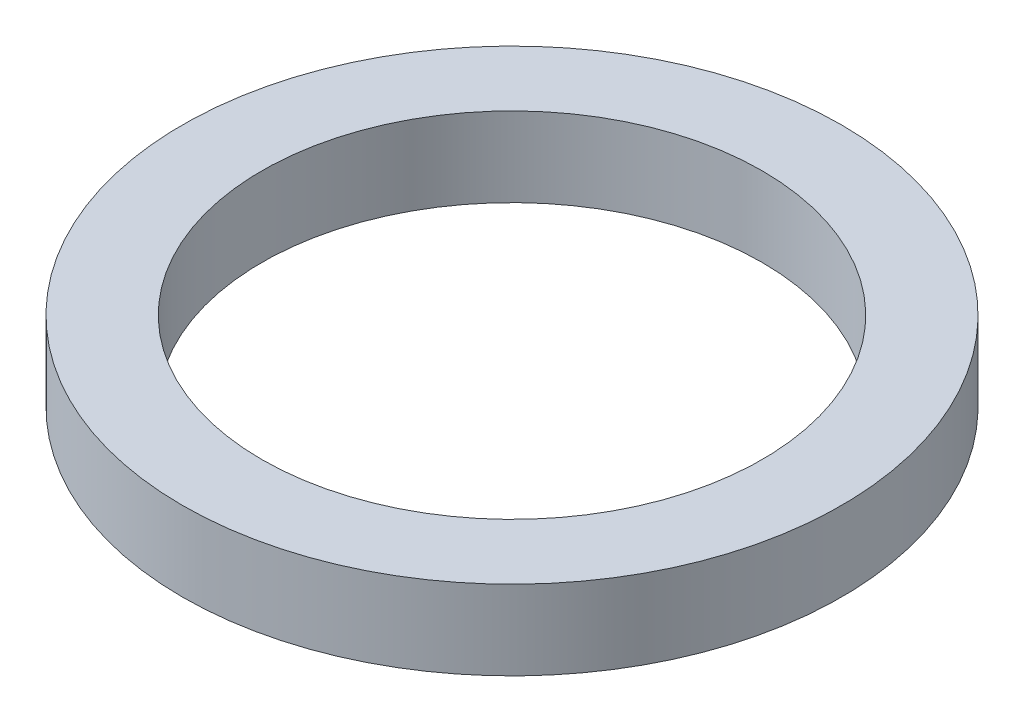
SolidWorks part; units mm, degrees
ref_plane "Front Plane" through (0, 0, 0) normal (0, 0, 1) x (1, 0, 0)
ref_plane "Top Plane" through (0, 0, 0) normal (0, 1, 0) x (1, 0, 0)
ref_plane "Right Plane" through (0, 0, 0) normal (1, 0, 0) x (0, 0, -1)
sketch "Sketch1" plane through (0, 0, 0) normal (0, 1, 0) x (1, 0, 0)
  circle A0 centre (0, 0) radius 4
  circle A1 centre (0, 0) radius 5.27
  dimension "D1" = 8
  dimension "D2" = 1.27
extrude "Boss-Extrude1" add sketch "Sketch1" along normal blind 1.27
